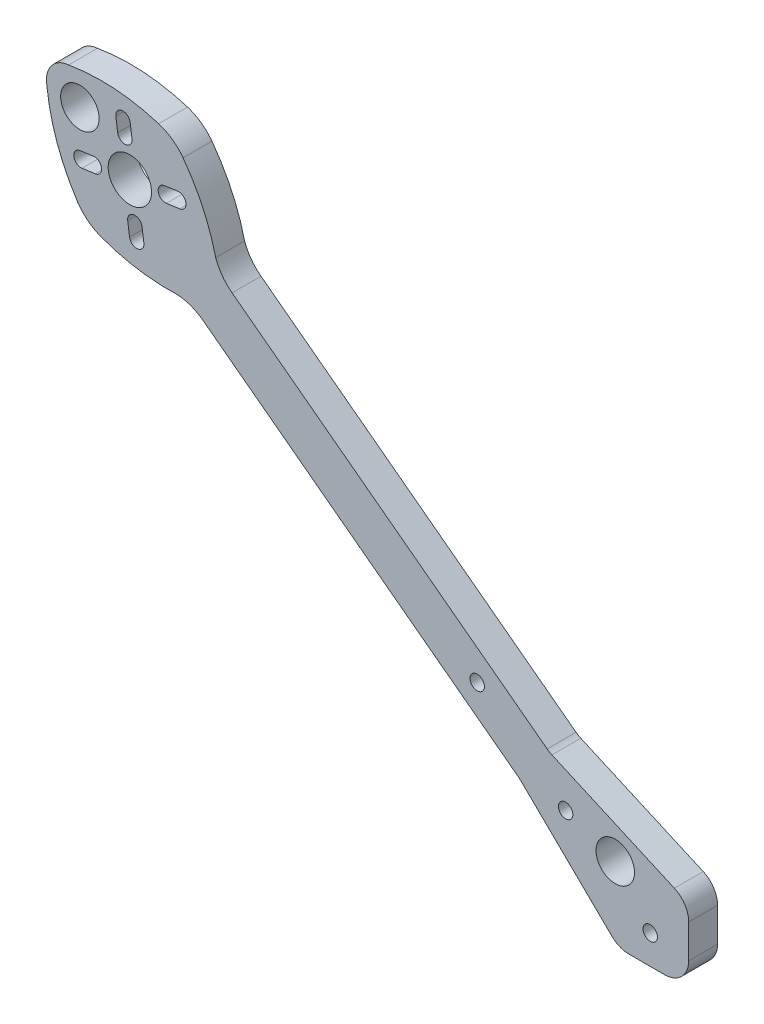
SolidWorks part; units mm, degrees
material "Thornel Mat VMA"
ref_plane "Alzado" through (0, 0, 0) normal (0, 0, 1) x (1, 0, 0)
ref_plane "Planta" through (0, 0, 0) normal (0, 1, 0) x (1, 0, 0)
ref_plane "Vista lateral" through (0, 0, 0) normal (1, 0, 0) x (0, 0, -1)
sketch "Croquis1" plane through (0, 0, 0) normal (0, 0, 1) x (1, 0, 0)
  line L0 (-177.8477, 93.6572) -> (-181.6394, 96.5144) construction
  line L1 (-181.6394, 96.5144) -> (-187.6575, 88.5281) construction
  line L2 (-187.6575, 88.5281) -> (-183.5551, 85.4367) construction
  line L3 (-148.4525, 70.2456) -> (-148.4525, 77.2417)
  line L4 (-151.4277, 81.8133) -> (-176.8634, 93.0787)
  line L5 (-148.4525, 65.2456) -> (-264.512, 152.7028) construction
  line L6 (-153.4525, 65.2456) -> (-160.8813, 65.2456)
  line L7 (-164.3783, 66.6719) -> (-183.3247, 85.2112)
  line L8 (-264.512, 152.7028) -> (-274.8943, 160.5264) construction
  line L9 (-264.512, 152.7028) -> (-266.1473, 164.3384) construction
  line L11 (-267.4239, 162.6443) -> (-267.0343, 159.8715)
  line L15 (-264.0635, 160.289) -> (-264.4531, 163.0618)
  line L19 (-267.6327, 164.1297) -> (-267.4239, 162.6443) construction
  line L20 (-267.4239, 162.6443) -> (-264.4531, 163.0618) construction
  line L21 (-266.8255, 158.3861) -> (-267.0343, 159.8715) construction
  line L22 (-267.0343, 159.8715) -> (-264.0635, 160.289) construction
  line L23 (-254.5705, 155.6147) -> (-257.3433, 155.225)
  line L24 (-256.9258, 152.2542) -> (-254.153, 152.6439)
  line L25 (-261.6001, 142.7613) -> (-261.9898, 145.534)
  line L26 (-264.9606, 145.1165) -> (-264.5709, 142.3438)
  line L27 (-274.4535, 149.7908) -> (-271.6808, 150.1805)
  line L28 (-272.0983, 153.1513) -> (-274.871, 152.7616)
  line L29 (-183.8125, 85.6307) -> (-249.3006, 134.9795)
  line L30 (-264.512, 152.7028) -> (-273.5392, 140.7232) construction
  line L31 (-263.0855, 142.5525) -> (-262.8767, 141.0671) construction
  line L32 (-274.8943, 160.5264) -> (-282.8806, 166.5445) construction
  line L33 (-262.8767, 141.0671) -> (-262.3693, 137.4568) construction
  line L34 (-274.6623, 151.2762) -> (-276.1477, 151.0675) construction
  line L35 (-276.1477, 151.0675) -> (-279.6136, 150.5804) construction
  line L36 (-177.5369, 93.423) -> (-243.2825, 142.9659)
  line L37 (-187.2342, 205.2976) -> (-187.2342, 100.7304) construction
  circle A0 centre (-192.3774, 98.3455) radius 1.5
  circle A1 centre (-174.0128, 84.5067) radius 1.5
  circle A2 centre (-163.7025, 80.4956) radius 4
  circle A3 centre (-156.4388, 71.2638) radius 1.5
  circle A5 centre (-148.4525, 65.2456) radius 10 construction
  circle A6 centre (-148.4525, 65.2456) radius 145.3223 construction
  circle A7 centre (-264.512, 152.7028) radius 4.5
  circle A8 centre (-274.8943, 160.5264) radius 4
  arc A9 (-267.4239, 162.6443) -> (-264.4531, 163.0618) centre (-265.9385, 162.853) cw
  arc A10 (-267.0343, 159.8715) -> (-264.0635, 160.289) centre (-265.5489, 160.0803) ccw
  arc A11 (-254.5705, 155.6147) -> (-254.153, 152.6439) centre (-254.3618, 154.1293) cw
  arc A12 (-257.3433, 155.225) -> (-256.9258, 152.2542) centre (-257.1345, 153.7396) ccw
  arc A13 (-261.6001, 142.7613) -> (-264.5709, 142.3438) centre (-263.0855, 142.5525) cw
  arc A14 (-261.9898, 145.534) -> (-264.9606, 145.1165) centre (-263.4752, 145.3253) ccw
  arc A15 (-274.4535, 149.7908) -> (-274.871, 152.7616) centre (-274.6623, 151.2762) cw
  arc A16 (-271.6808, 150.1805) -> (-272.0983, 153.1513) centre (-271.8895, 151.6659) ccw
  arc A17 (-249.3006, 134.9795) -> (-254.6905, 136.9734) centre (-255.3188, 126.9931) ccw
  arc A18 (-254.6905, 136.9734) -> (-270.5641, 139.4702) centre (-256.5386, 176.9307) cw
  arc A19 (-277.233, 166.9825) -> (-281.7449, 160.995) centre (-276.8465, 161.9974) ccw
  arc A20 (-281.7449, 160.995) -> (-275.418, 143.3485) centre (-241.9768, 165.2959) ccw
  arc A21 (-270.5641, 139.4702) -> (-275.418, 143.3485) centre (-267.0577, 148.8353) cw
  arc A22 (-243.2825, 142.9659) -> (-246.6848, 147.5973) centre (-237.2643, 150.9522) cw
  arc A23 (-246.6848, 147.5973) -> (-253.4602, 162.1678) centre (-285.6036, 138.3601) ccw
  arc A24 (-253.4602, 162.1678) -> (-258.5262, 165.7647) centre (-261.4961, 156.2159) ccw
  arc A25 (-277.233, 166.9825) -> (-258.5262, 165.7647) centre (-270.4057, 127.5694) cw
  arc A26 (-160.8813, 65.2456) -> (-164.3783, 66.6719) centre (-160.8813, 70.2456) cw
  arc A27 (-148.4525, 70.2456) -> (-153.4525, 65.2456) centre (-153.4525, 70.2456) cw
  arc A28 (-148.4525, 77.2417) -> (-151.4277, 81.8133) centre (-153.4525, 77.2417) ccw
  arc A29 (-177.8477, 93.6572) -> (-176.8634, 93.0787) centre (-174.8387, 97.6504) ccw
  arc A30 (-183.3247, 85.2112) -> (-183.8125, 85.6307) centre (-186.8216, 81.6375) ccw
  circle A32 centre (-264.512, 152.7028) radius 77 construction
  point P52 (-264.512, 152.7028)
  point P60 (-263.4186, 145.6182)
  point P80 (-162.9207, 65.2456)
  point P86 (-148.4525, 80.4956)
  dimension "D1" = 45
  dimension "D17" = 8
  dimension "D18" = 9
  dimension "D21" = 10
  dimension "D23" = 40
  dimension "D24" = 5
  dimension "D25" = 10
  dimension "D26" = 5
  dimension "D10" = 8
  dimension "D35" = 8.4146
  dimension "D39" = 11.7531
  dimension "D2" = 11.75
  dimension "D3" = 3
  dimension "D4" = 4
  dimension "D5" = 1.5
  dimension "D6" = 10
  dimension "D7" = 32.0049
  dimension "D8" = 21.5668
  dimension "D9" = 3.0015
  dimension "D11" = 82
  dimension "D12" = 22.9951
  dimension "D13" = 14.4682
  dimension "D14" = 15.25
  dimension "D15" = 100
  dimension "D16" = 13
  dimension "D19" = 10
  dimension "D20" = 15
  dimension "D22" = 5
  dimension "D27" = 18.5439
  dimension "D28" = 36.4193
  dimension "D29" = 14.4957
  dimension "D30" = 13.3026
  dimension "D31" = 15.8736
  dimension "D32" = 14.5704
  dimension "D33" = 3.8783
  dimension "D34" = 17.6465
  dimension "D36" = 10.2091
  dimension "D37" = 0.6434
  dimension "D38" = 9.5875
extrude "Saliente-Extruir1" add sketch "Croquis1" along normal blind 6
